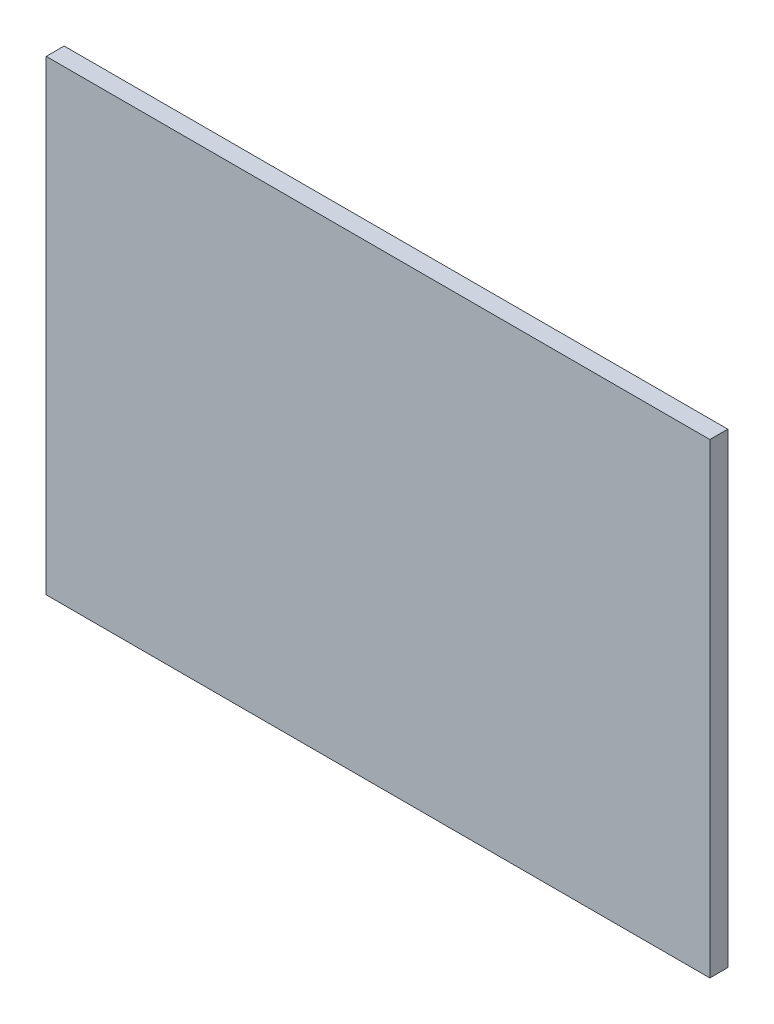
SolidWorks part; units mm, degrees
ref_plane "Alzado" through (0, 0, 0) normal (0, 0, 1) x (1, 0, 0)
ref_plane "Planta" through (0, 0, 0) normal (0, 1, 0) x (1, 0, 0)
ref_plane "Vista lateral" through (0, 0, 0) normal (1, 0, 0) x (0, 0, -1)
sketch "Croquis1" plane through (0, 0, 0) normal (0, 0, 1) x (1, 0, 0)
  line L1 (-37, -26) -> (37, -26)
  line L2 (-37, -26) -> (-37, 26)
  line L3 (-37, 26) -> (37, 26)
  line L4 (37, -26) -> (37, 26)
  line L5 (-37, -26) -> (37, 26) construction
  line L6 (-37, 26) -> (37, -26) construction
  point P0 (0, 0)
  dimension "D1" = 74
  dimension "D2" = 52
extrude "Saliente-Extruir1" add sketch "Croquis1" along normal blind 2
